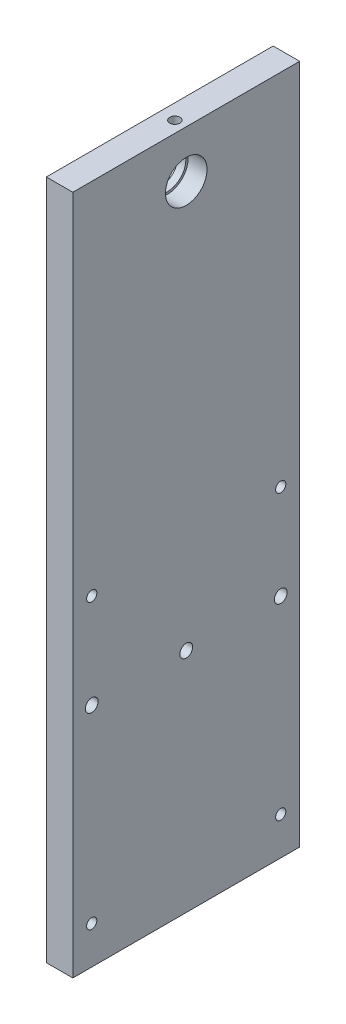
SolidWorks part; units mm, degrees
ref_plane "前基準面" through (0, 0, 0) normal (0, 0, 1) x (1, 0, 0)
ref_plane "上基準面" through (0, 0, 0) normal (0, 1, 0) x (1, 0, 0)
ref_plane "右基準面" through (0, 0, 0) normal (1, 0, 0) x (0, 0, -1)
sketch "草圖1" plane through (0, 0, 0) normal (1, 0, 0) x (0, 0, -1)
  line L1 (-30, -90) -> (30, -90)
  line L2 (-30, -90) -> (-30, 90)
  line L3 (-30, 90) -> (30, 90)
  line L4 (30, -90) -> (30, 90)
  line L5 (-30, -90) -> (30, 90) construction
  line L6 (-30, 90) -> (30, -90) construction
  point P0 (0, 0)
  dimension "D1" = 180
  dimension "D2" = 60
extrude "填料-伸長1" add sketch "草圖1" along normal blind 7
sketch "草圖2" plane through (7, 0, 0) normal (1, 0, 0) x (0, 0, -1)
  line L0 (30, 90) -> (-30, 90) construction
  circle A0 centre (0, 77.5) radius 5.5
  dimension "D1" = 11
  dimension "D2" = 12.5
extrude "除料-伸長1" cut sketch "草圖2" against normal blind 5
sketch "草圖3" plane through (2, 0, 0) normal (1, 0, 0) x (0, 0, -1)
  circle A0 centre (0, 77.5) radius 4.9
  dimension "D1" = 9.8
extrude "除料-伸長2" cut sketch "草圖3" against normal through all
hole_wizard "M3 錐坑平頭螺釘的錐孔1" positions "草圖4" profile "草圖5" countersink size "M3" standard "ISO"
sketch "草圖4" plane through (0, 0, 0) normal (-1, 0, 0) x (0, 0, 1)
  line L0 (30, -90) -> (-30, -90) construction
  point P0 (-25, -30)
  point P2 (0, -30)
  point P4 (25, -30)
  dimension "D1" = 25
  dimension "D2" = 25
  dimension "D3" = 60
sketch "草圖5" plane through (0, -30, -25) normal (0, 1, 0) x (0, 0, 1)
  line L0 (0, 0) -> (0, 8.5215)
  line L1 (0, 8.5215) -> (1.7, 7.5)
  line L2 (1.7, 7.5) -> (1.7, 1.45)
  line L3 (1.7, 1.45) -> (3.15, 0)
  line L5 (3.15, 0) -> (0, 0)
  line L6 (-1.7, 1.45) -> (-3.15, 0) construction
  line L10 (0, 8.5215) -> (-1.7, 7.5) construction
  line L11 (0, -6.35) -> (0, 107.95) construction
  dimension "鑽孔直徑" = 3.4
  dimension "鑽孔深度" = 7.5
  dimension "近端錐孔直徑" = 6.3
  dimension "近端錐孔角度" = 90
  dimension "導頭角度" = 118
hole_wizard "Ø1.0mm 定位孔3" positions "草圖8" profile "草圖9" hole size "Ø1.0" standard "ISO"
sketch "草圖8" plane through (0, 90, 0) normal (0, 1, 0) x (1, 0, 0)
  line L0 (7, 30) -> (7, -30) construction
  point P0 (4, 0)
  dimension "D1" = 3
sketch "草圖9" plane through (4, 90, 0) normal (1, 0, 0) x (0, 0, 1)
  line L0 (0, 0) -> (0, 7)
  line L1 (0, 7) -> (1.35, 7)
  line L2 (1.35, 7) -> (1.35, 0)
  line L5 (1.35, 0) -> (0, 0)
  line L11 (0, -6.35) -> (0, 107.95) construction
  dimension "貫穿孔直徑" = 2.7
  dimension "貫穿孔深度" = 7
hole_wizard "Ø1.0mm 定位孔2" positions "草圖10" profile "草圖11" hole size "Ø1.0" standard "ISO"
sketch "草圖10" plane through (0, -90, 0) normal (0, -1, 0) x (-1, 0, 0)
  line L0 (-3.5, 25) -> (-3.5, 30) construction
  line L1 (-7, 30) -> (0, 30) construction
  point P0 (-3.5, 25)
  point P2 (-3.5, 0)
  point P4 (-3.5, -25)
  dimension "D1" = 25
  dimension "D2" = 25
sketch "草圖11" plane through (3.5, -90, -25) normal (1, 0, 0) x (0, 0, -1)
  line L0 (0, 0) -> (0, 8.3112)
  line L1 (0, 8.3112) -> (1.35, 7.5)
  line L2 (1.35, 7.5) -> (1.35, 0)
  line L5 (1.35, 0) -> (0, 0)
  line L10 (0, 8.3112) -> (-1.35, 7.5) construction
  line L11 (0, -6.35) -> (0, 107.95) construction
  dimension "鑽孔直徑" = 2.7
  dimension "鑽孔深度" = 7.5
  dimension "導頭角度" = 118
hole_wizard "Ø1.0mm 定位孔1" positions "草圖12" profile "草圖13" hole size "Ø1.0" standard "ISO" end condition through all
sketch "草圖12" plane through (0, 0, 0) normal (-1, 0, 0) x (0, 0, 1)
  line L0 (30, -90) -> (-30, -90) construction
  line L1 (30, 90) -> (30, -90) construction
  point P0 (25, -5)
  point P2 (25, -80)
  point P8 (-25, -80)
  point P10 (-25, -5)
  dimension "D1" = 75
  dimension "D2" = 10
  dimension "D3" = 5
  dimension "D4" = 50
sketch "草圖13" plane through (0, -5, 25) normal (0, 1, 0) x (0, 0, 1)
  line L0 (0, 0) -> (0, 7)
  line L1 (0, 7) -> (1.35, 7)
  line L2 (1.35, 7) -> (1.35, 0)
  line L5 (1.35, 0) -> (0, 0)
  line L11 (0, -6.35) -> (0, 107.95) construction
  dimension "貫穿孔直徑" = 2.7
  dimension "貫穿孔深度" = 7
